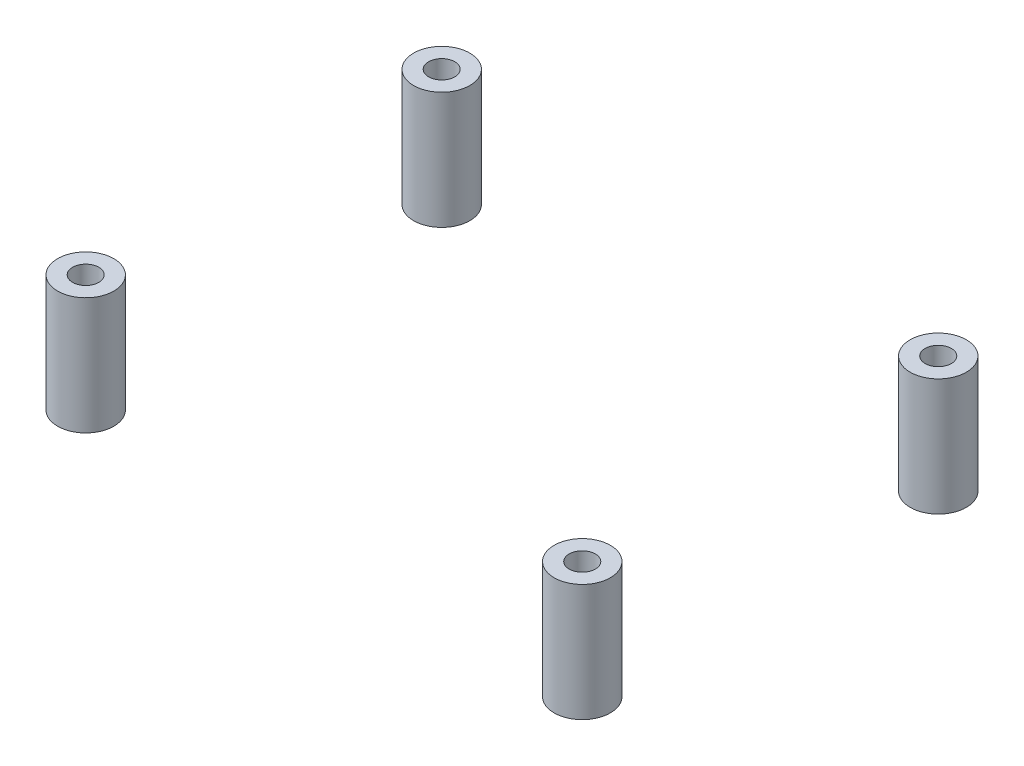
SolidWorks part; units mm, degrees
ref_plane "Front Plane" through (0, 0, 0) normal (0, 0, 1) x (1, 0, 0)
ref_plane "Top Plane" through (0, 0, 0) normal (0, 1, 0) x (1, 0, 0)
ref_plane "Right Plane" through (0, 0, 0) normal (1, 0, 0) x (0, 0, -1)
sketch "Sketch1" plane through (0, 0, 0) normal (0, 1, 0) x (1, 0, 0)
  line L0 (-34.2353, 23.9287) -> (-34.2353, -14.0713) construction
  line L1 (-37.7353, 27.4287) -> (22.2647, 27.4287)
  line L2 (-37.7353, 27.4287) -> (-37.7353, -17.5713)
  line L3 (-37.7353, -17.5713) -> (22.2647, -17.5713)
  line L4 (22.2647, 27.4287) -> (22.2647, -17.5713)
  line L5 (-34.2353, -14.0713) -> (18.7647, -14.0713) construction
  line L6 (-47.7353, 32.4287) -> (-47.7353, -49.5713) construction
  line L7 (77.2647, 32.4287) -> (-42.7353, 32.4287) construction
  circle A0 centre (-34.2353, -14.0713) radius 3
  circle A1 centre (18.7647, -14.0713) radius 3
  circle A2 centre (18.7647, 23.9287) radius 3
  circle A3 centre (-34.2353, 23.9287) radius 3
  point P12 (-7.7353, -17.5713)
  point P13 (-7.7353, -14.0713)
  point P14 (-37.7353, 4.9287)
  point P15 (-34.2353, 4.9287)
  point P16 (0, 0)
  point P17 (0, 0)
  dimension "D3" = 6
  dimension "D1" = 60
  dimension "D2" = 45
  dimension "D4" = 53
  dimension "D5" = 38
  dimension "D6" = 10
  dimension "D7" = 5
extrude "Boss-Extrude1" add sketch "Sketch1" along normal blind 12.5 contours A3 | A0 | A1 | A2
sketch "Sketch2" plane through (0, 12.5, 0) normal (0, 1, 0) x (1, 0, 0)
  circle A0 centre (-34.2353, 23.9287) radius 1.4
  circle A1 centre (18.7647, 23.9287) radius 1.4
  circle A2 centre (18.7647, -14.0713) radius 1.4
  circle A3 centre (-34.2353, -14.0713) radius 1.4
  dimension "D1" = 2.8
extrude "Cut-Extrude1" cut sketch "Sketch2" against normal blind 10
